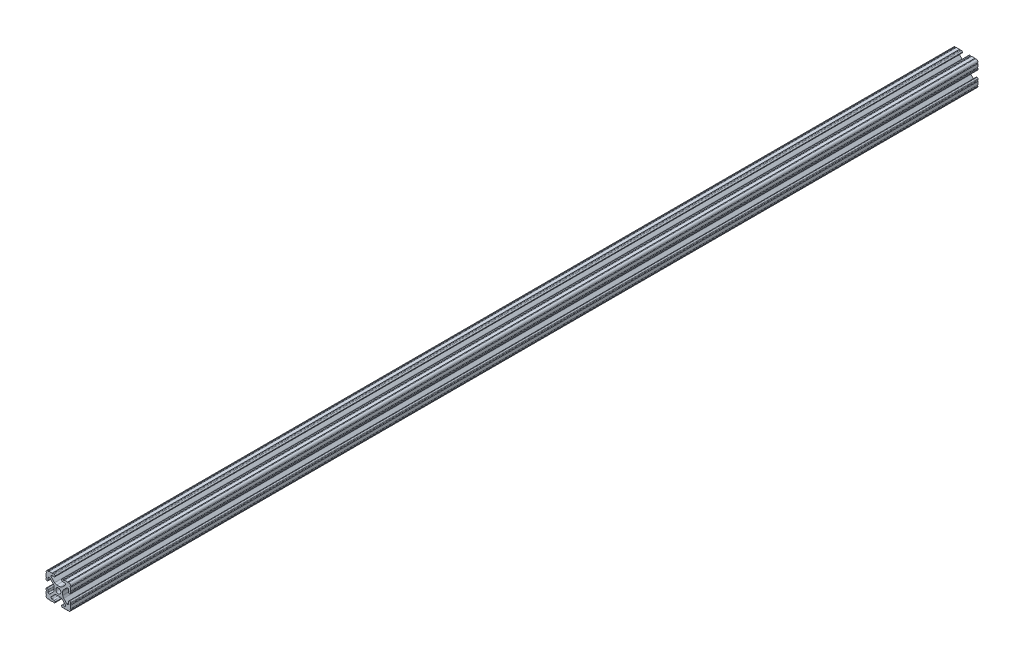
SolidWorks part; units mm, degrees
ref_plane "Front Plane" through (0, 0, 0) normal (0, 0, 1) x (1, 0, 0)
ref_plane "Top Plane" through (0, 0, 0) normal (0, 1, 0) x (1, 0, 0)
ref_plane "Right Plane" through (0, 0, 0) normal (1, 0, 0) x (0, 0, -1)
sketch "Sketch1" plane through (0, 0, 0) normal (0, 0, 1) x (1, 0, 0)
  line L88 (-7.1797, -8.6452) -> (-3.9523, -5.4237)
  line L89 (-1.7093, -4.4958) -> (1.7093, -4.4958)
  line L90 (3.9523, -5.4237) -> (7.1797, -8.6452)
  line L91 (6.4164, -10.4902) -> (4.2875, -10.4902)
  line L92 (3.2385, -11.5392) -> (3.2385, -11.651)
  line L93 (4.2875, -12.7) -> (5.3171, -12.7)
  line L94 (6.3331, -12.7) -> (9.5504, -12.7)
  line L95 (12.7, -9.5504) -> (12.7, -6.3331)
  line L96 (12.7, -5.3171) -> (12.7, -4.2875)
  line L97 (11.651, -3.2385) -> (11.5392, -3.2385)
  line L98 (10.4902, -4.2875) -> (10.4902, -6.4021)
  line L99 (8.7371, -7.1294) -> (5.441, -3.8408)
  line L100 (4.5085, -1.5932) -> (4.5085, 1.5932)
  line L101 (5.441, 3.8408) -> (8.7371, 7.1294)
  line L102 (10.4902, 6.4021) -> (10.4902, 4.2875)
  line L103 (11.5392, 3.2385) -> (11.651, 3.2385)
  line L104 (12.7, 4.2875) -> (12.7, 5.3171)
  line L105 (12.7, 6.3331) -> (12.7, 9.5504)
  line L106 (9.5504, 12.7) -> (6.3331, 12.7)
  line L107 (5.3171, 12.7) -> (4.2875, 12.7)
  line L108 (3.2385, 11.651) -> (3.2385, 11.5392)
  line L109 (4.2875, 10.4902) -> (6.4768, 10.4902)
  line L110 (7.207, 8.7244) -> (3.8983, 5.4232)
  line L111 (1.6558, 4.4958) -> (-1.6558, 4.4958)
  line L112 (-3.8983, 5.4232) -> (-7.207, 8.7244)
  line L113 (-6.4768, 10.4902) -> (-4.2875, 10.4902)
  line L114 (-3.2385, 11.5392) -> (-3.2385, 11.651)
  line L115 (-4.2875, 12.7) -> (-5.3171, 12.7)
  line L116 (-6.3331, 12.7) -> (-9.5504, 12.7)
  line L117 (-12.7, 9.5504) -> (-12.7, 6.3331)
  line L118 (-12.7, 5.3171) -> (-12.7, 4.2875)
  line L119 (-11.651, 3.2385) -> (-11.5392, 3.2385)
  line L120 (-10.4902, 4.2875) -> (-10.4902, 6.4021)
  line L121 (-8.7371, 7.1294) -> (-5.441, 3.8408)
  line L122 (-4.5085, 1.5932) -> (-4.5085, -1.5932)
  line L123 (-5.441, -3.8408) -> (-8.7371, -7.1294)
  line L124 (-10.4902, -6.4021) -> (-10.4902, -4.2875)
  line L125 (-11.5392, -3.2385) -> (-11.651, -3.2385)
  line L126 (-12.7, -4.2875) -> (-12.7, -5.3171)
  line L127 (-12.7, -6.3331) -> (-12.7, -9.5504)
  line L128 (-9.5504, -12.7) -> (-6.3331, -12.7)
  line L129 (-5.3171, -12.7) -> (-4.2875, -12.7)
  line L130 (-3.2385, -11.651) -> (-3.2385, -11.5392)
  line L131 (-4.2875, -10.4902) -> (-6.4164, -10.4902)
  circle A1 centre (0, 0) radius 2.6035
  arc A104 (-7.1797, -8.6452) -> (-6.4164, -10.4902) centre (-6.4164, -9.4098) ccw
  arc A105 (-1.7093, -4.4958) -> (-3.9523, -5.4237) centre (-1.7093, -7.6708) ccw
  arc A106 (3.9523, -5.4237) -> (1.7093, -4.4958) centre (1.7093, -7.6708) ccw
  arc A107 (6.4164, -10.4902) -> (7.1797, -8.6452) centre (6.4164, -9.4098) ccw
  arc A108 (4.2875, -10.4902) -> (3.2385, -11.5392) centre (4.2875, -11.5392) ccw
  arc A109 (3.2385, -11.651) -> (4.2875, -12.7) centre (4.2875, -11.651) ccw
  arc A110 (6.3331, -12.7) -> (5.3171, -12.7) centre (5.8251, -12.7) ccw
  arc A111 (10.5664, -12.6998) -> (9.5504, -12.7) centre (10.0584, -12.7) ccw
  arc A112 (10.5664, -12.6998) -> (12.6998, -10.5664) centre (10.5918, -10.5918) ccw
  arc A113 (12.7, -9.5504) -> (12.6998, -10.5664) centre (12.7, -10.0584) ccw
  arc A114 (12.7, -5.3171) -> (12.7, -6.3331) centre (12.7, -5.8251) ccw
  arc A115 (12.7, -4.2875) -> (11.651, -3.2385) centre (11.651, -4.2875) ccw
  arc A116 (11.5392, -3.2385) -> (10.4902, -4.2875) centre (11.5392, -4.2875) ccw
  arc A117 (8.7371, -7.1294) -> (10.4902, -6.4021) centre (9.4628, -6.4021) ccw
  arc A118 (4.5085, -1.5932) -> (5.441, -3.8408) centre (7.6835, -1.5932) ccw
  arc A119 (5.441, 3.8408) -> (4.5085, 1.5932) centre (7.6835, 1.5932) ccw
  arc A120 (10.4902, 6.4021) -> (8.7371, 7.1294) centre (9.4628, 6.4021) ccw
  arc A121 (10.4902, 4.2875) -> (11.5392, 3.2385) centre (11.5392, 4.2875) ccw
  arc A122 (11.651, 3.2385) -> (12.7, 4.2875) centre (11.651, 4.2875) ccw
  arc A123 (12.7, 6.3331) -> (12.7, 5.3171) centre (12.7, 5.8251) ccw
  arc A124 (12.6998, 10.5664) -> (12.7, 9.5504) centre (12.7, 10.0584) ccw
  arc A125 (12.6998, 10.5664) -> (10.5664, 12.6998) centre (10.5918, 10.5918) ccw
  arc A126 (9.5504, 12.7) -> (10.5664, 12.6998) centre (10.0584, 12.7) ccw
  arc A127 (5.3171, 12.7) -> (6.3331, 12.7) centre (5.8251, 12.7) ccw
  arc A128 (4.2875, 12.7) -> (3.2385, 11.651) centre (4.2875, 11.651) ccw
  arc A129 (3.2385, 11.5392) -> (4.2875, 10.4902) centre (4.2875, 11.5392) ccw
  arc A130 (7.207, 8.7244) -> (6.4768, 10.4902) centre (6.4768, 9.4563) ccw
  arc A131 (1.6558, 4.4958) -> (3.8983, 5.4232) centre (1.6558, 7.6708) ccw
  arc A132 (-3.8983, 5.4232) -> (-1.6558, 4.4958) centre (-1.6558, 7.6708) ccw
  arc A133 (-6.4768, 10.4902) -> (-7.207, 8.7244) centre (-6.4768, 9.4563) ccw
  arc A134 (-4.2875, 10.4902) -> (-3.2385, 11.5392) centre (-4.2875, 11.5392) ccw
  arc A135 (-3.2385, 11.651) -> (-4.2875, 12.7) centre (-4.2875, 11.651) ccw
  arc A136 (-6.3331, 12.7) -> (-5.3171, 12.7) centre (-5.8251, 12.7) ccw
  arc A137 (-10.5664, 12.6998) -> (-9.5504, 12.7) centre (-10.0584, 12.7) ccw
  arc A138 (-10.5664, 12.6998) -> (-12.6998, 10.5664) centre (-10.5918, 10.5918) ccw
  arc A139 (-12.7, 9.5504) -> (-12.6998, 10.5664) centre (-12.7, 10.0584) ccw
  arc A140 (-12.7, 5.3171) -> (-12.7, 6.3331) centre (-12.7, 5.8251) ccw
  arc A141 (-12.7, 4.2875) -> (-11.651, 3.2385) centre (-11.651, 4.2875) ccw
  arc A142 (-11.5392, 3.2385) -> (-10.4902, 4.2875) centre (-11.5392, 4.2875) ccw
  arc A143 (-8.7371, 7.1294) -> (-10.4902, 6.4021) centre (-9.4628, 6.4021) ccw
  arc A144 (-4.5085, 1.5932) -> (-5.441, 3.8408) centre (-7.6835, 1.5932) ccw
  arc A145 (-5.441, -3.8408) -> (-4.5085, -1.5932) centre (-7.6835, -1.5932) ccw
  arc A146 (-10.4902, -6.4021) -> (-8.7371, -7.1294) centre (-9.4628, -6.4021) ccw
  arc A147 (-10.4902, -4.2875) -> (-11.5392, -3.2385) centre (-11.5392, -4.2875) ccw
  arc A148 (-11.651, -3.2385) -> (-12.7, -4.2875) centre (-11.651, -4.2875) ccw
  arc A149 (-12.7, -6.3331) -> (-12.7, -5.3171) centre (-12.7, -5.8251) ccw
  arc A150 (-12.6998, -10.5664) -> (-12.7, -9.5504) centre (-12.7, -10.0584) ccw
  arc A151 (-12.6998, -10.5664) -> (-10.5664, -12.6998) centre (-10.5918, -10.5918) ccw
  arc A152 (-9.5504, -12.7) -> (-10.5664, -12.6998) centre (-10.0584, -12.7) ccw
  arc A153 (-5.3171, -12.7) -> (-6.3331, -12.7) centre (-5.8251, -12.7) ccw
  arc A154 (-4.2875, -12.7) -> (-3.2385, -11.651) centre (-4.2875, -11.651) ccw
  arc A155 (-3.2385, -11.5392) -> (-4.2875, -10.4902) centre (-4.2875, -11.5392) ccw
extrude "Boss-Extrude1" add sketch "Sketch1" along normal mid plane 933.45
sketch "Sketch2" plane through (4.5085, 0, 0) normal (1, 0, 0) x (0, 0, -1)
  line L0 (0, 0) -> (-393.7, 0) construction
  line L1 (-466.725, -1.5932) -> (-466.725, 1.5932) construction
  line L2 (0, 0) -> (0, 58.4486) construction
  line L3 (-466.725, 6.3331) -> (-466.725, 9.5504) construction
  circle A0 centre (-231.775, 0) radius 3.175
  circle A1 centre (231.775, 0) radius 3.175
  circle A2 centre (-85.725, 0) radius 3.175
  circle A3 centre (85.725, 0) radius 3.175
  dimension "D1" = 6.35
  dimension "D2" = 234.95
  dimension "D3" = 6.35
  dimension "D4" = 381
extrude "Cut-Extrude1" cut sketch "Sketch2" against normal through all both and the other way through all
